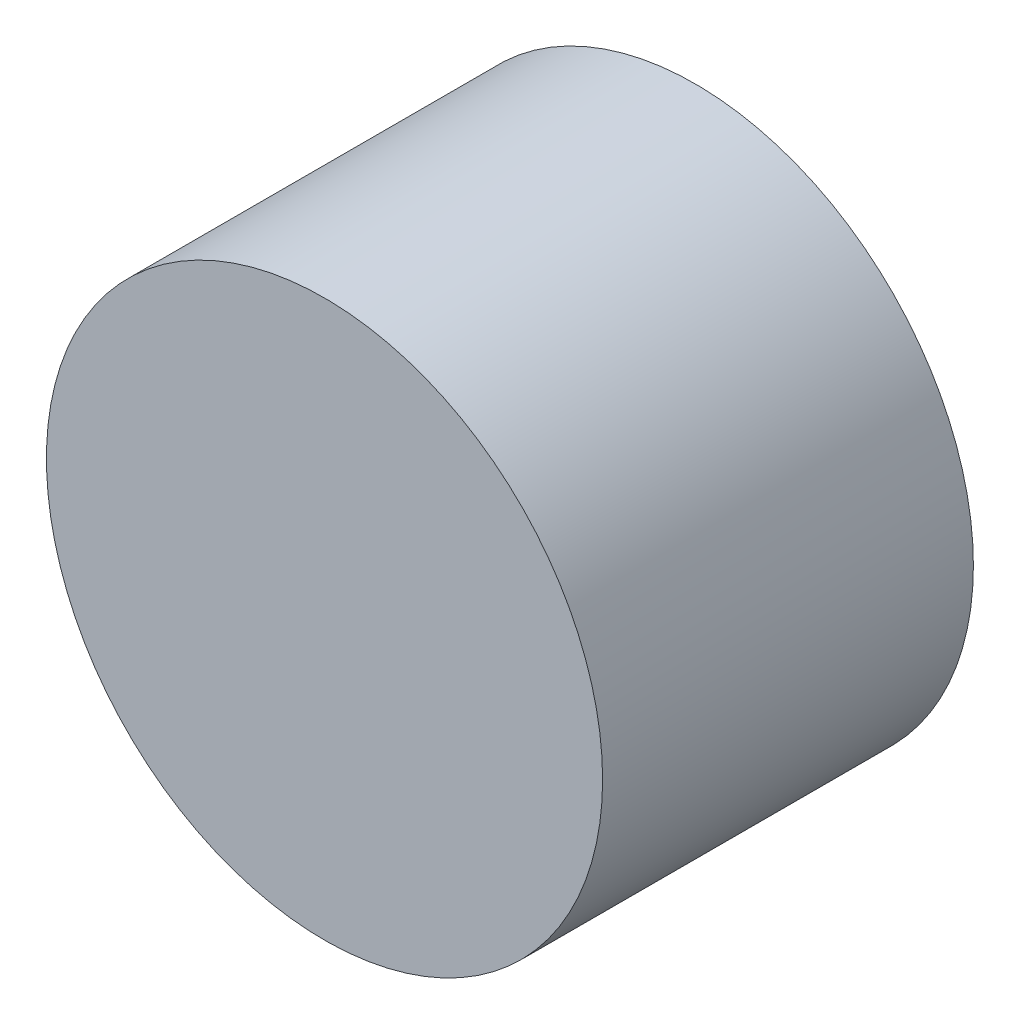
SolidWorks part; units mm, degrees
ref_plane "Front Plane" through (0, 0, 0) normal (0, 0, 1) x (1, 0, 0)
ref_plane "Top Plane" through (0, 0, 0) normal (0, 1, 0) x (1, 0, 0)
ref_plane "Right Plane" through (0, 0, 0) normal (1, 0, 0) x (0, 0, -1)
sketch "Sketch1" plane through (0, 0, 0) normal (0, 0, 1) x (1, 0, 0)
  circle A0 centre (0, 0) radius 6
extrude "Retaining_Cap_12OD_8L" add sketch "Sketch1" along normal blind 8 from offset 0
sketch "Sketch2" plane through (0, 0, 0) normal (0, 0, 1) x (1, 0, 0)
  circle A0 centre (0, 0) radius 4.2
extrude "Blind_Axle_Socket_8p4" cut sketch "Sketch2" along normal blind 5.6 from offset 0.1
